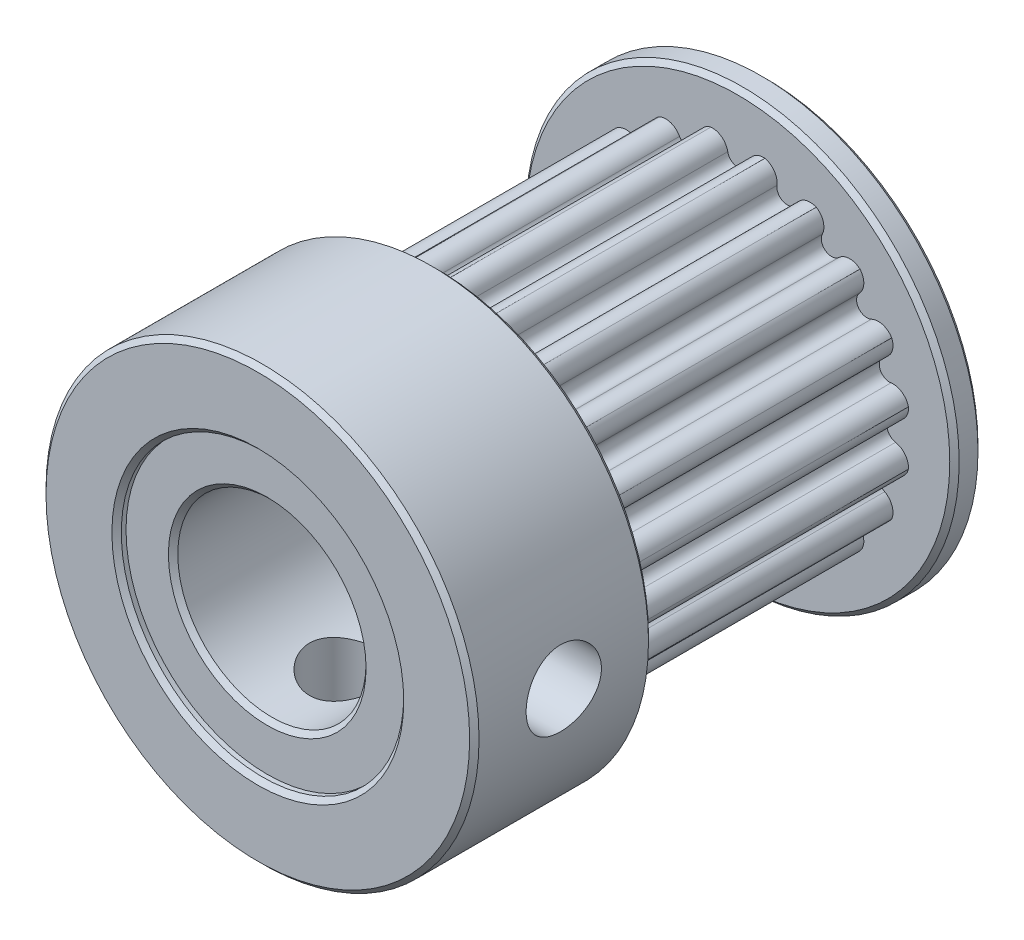
SolidWorks part; units mm, degrees
ref_plane "Plan de face" through (0, 0, 0) normal (0, 0, 1) x (1, 0, 0)
ref_plane "Plan de dessus" through (0, 0, 0) normal (0, 1, 0) x (1, 0, 0)
ref_plane "Plan de droite" through (0, 0, 0) normal (1, 0, 0) x (0, 0, -1)
sketch "Esquisse1" plane through (0, 0, 0) normal (0, 0, 1) x (1, 0, 0)
  circle A0 centre (0, 0) radius 11.5
  circle A1 centre (0, 0) radius 5
  dimension "D1" = 23
  dimension "D2" = 10
extrude "Boss.-Extru.1" add sketch "Esquisse1" along normal blind 27
ref_plane "Plan1" through (0, 0, 1.5) normal (0, 0, -1) x (-1, 0, 0)
sketch "Esquisse2" plane through (0, 0, 1.5) normal (0, 0, -1) x (-1, 0, 0)
  circle A0 centre (0, 0) radius 9.17
  circle A1 centre (0, 0) radius 11.5
  dimension "D1" = 18.34
extrude "Enlèv. mat.-Extru.1" cut sketch "Esquisse2" against normal blind 16
sketch "Esquisse3" plane through (0, 0, 17.5) normal (0, 0, -1) x (-1, 0, 0)
  line L0 (-10.9902, 9.17) -> (15.4189, 9.17) construction
  line L1 (0, 0) -> (0, 15.6348) construction
  line L2 (-1.0417, 7.92) -> (1.5586, 7.92) construction
  circle A0 centre (0, 0) radius 9.17 construction
  circle A1 centre (0, 0) radius 9.17 construction
  arc A2 (-1.5, 9.0465) -> (-0.5411, 8.3716) centre (-1.3633, 8.2221) cw
  arc A3 (-0.5411, 8.3716) -> (0.5411, 8.3716) centre (0, 8.47) ccw
  arc A4 (0.5411, 8.3716) -> (1.5, 9.0465) centre (1.3633, 8.2221) cw
  arc A5 (-1.5, 9.0465) -> (1.5, 9.0465) centre (0, 0) cw
  point P17 (0, 0)
  dimension "D2" = 0.55
  dimension "D1" = 1.25
  dimension "D3" = 3
extrude "Enlèv. mat.-Extru.2" cut sketch "Esquisse3" along normal up to surface (16 mm away) up to face at (-9.17, 0, 1.5)
pattern_circular "Répétition circulaire1" count 20 over 360 about axis through (0, 0, 0) along (0, 0, 1) of "Enlèv. mat.-Extru.2"
sketch "Esquisse4" plane through (0, 0, 0) normal (0, 1, 0) x (1, 0, 0)
  line L0 (0, 0) -> (0, -26.9226) construction
  line L3 (-11.5, -17.5) -> (17.9359, -17.5) construction
  line L4 (17.9359, -17.5) -> (17.9359, -27) construction
  line L5 (17.9359, -27) -> (-11.5, -27) construction
  line L6 (-11.5, -27) -> (11.5, -27) construction
  line L7 (0, -22.25) -> (29.4359, -22.25) construction
  circle A0 centre (0, -22.25) radius 2
  dimension "D1" = 4
extrude "Enlèv. mat.-Extru.3" cut sketch "Esquisse4" against normal blind 16
pattern_circular "Répétition circulaire2" count 2 over 90 about axis through (0, 0, 27) along (0, 0, -1) of "Enlèv. mat.-Extru.3"
sketch "Esquisse5" plane through (0, 0, 0) normal (0, 0, -1) x (-1, 0, 0)
  circle A0 centre (0, 0) radius 7.5
  dimension "D1" = 15
extrude "Enlèv. mat.-Extru.4" cut sketch "Esquisse5" against normal blind 0.5
ref_plane "Plan2" through (0, 0, 13.5) normal (0, 0, -1) x (-1, 0, 0)
mirror "Symétrie1" about plane through (0, 0, 13.5) normal (0, 0, -1) of "Enlèv. mat.-Extru.4"
chamfer "Chanfrein1" distance 0.25 angle 45 8 edges at (5, 0, 26.5) (-5, 0, 0.5) (-7.5, 0, 0) (11.5, 0, 0) (11.5, 0, 27) (-11.5, 0, 17.5) (-11.5, 0, 1.5) (-7.5, 0, 27)
